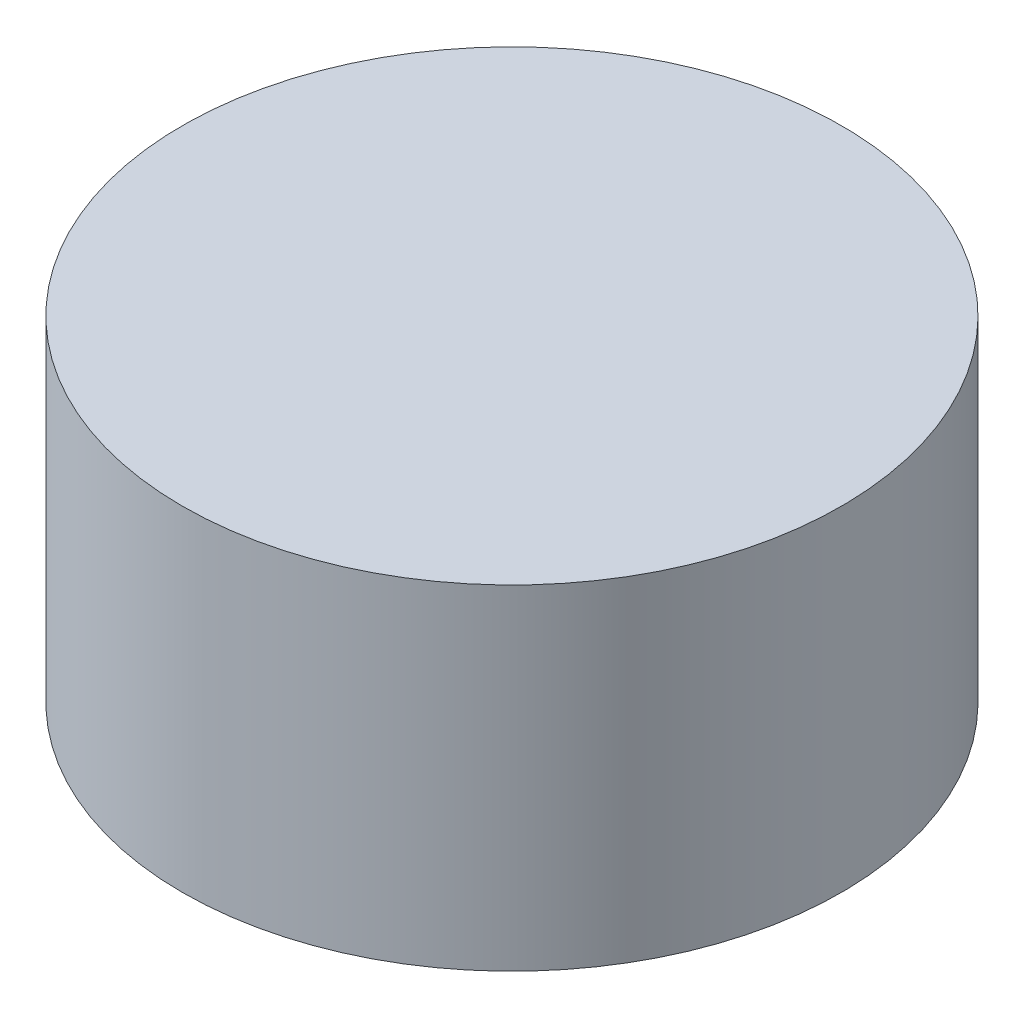
SolidWorks part; units mm, degrees
ref_plane "Front Plane" through (0, 0, 0) normal (0, 0, 1) x (1, 0, 0)
ref_plane "Top Plane" through (0, 0, 0) normal (0, 1, 0) x (1, 0, 0)
ref_plane "Right Plane" through (0, 0, 0) normal (1, 0, 0) x (0, 0, -1)
sketch "Sketch1" plane through (0, 0, 0) normal (0, 1, 0) x (1, 0, 0)
  circle A0 centre (0, 0) radius 78.2754
extrude "Boss-Extrude1" add sketch "Sketch1" along normal blind 79.4494
